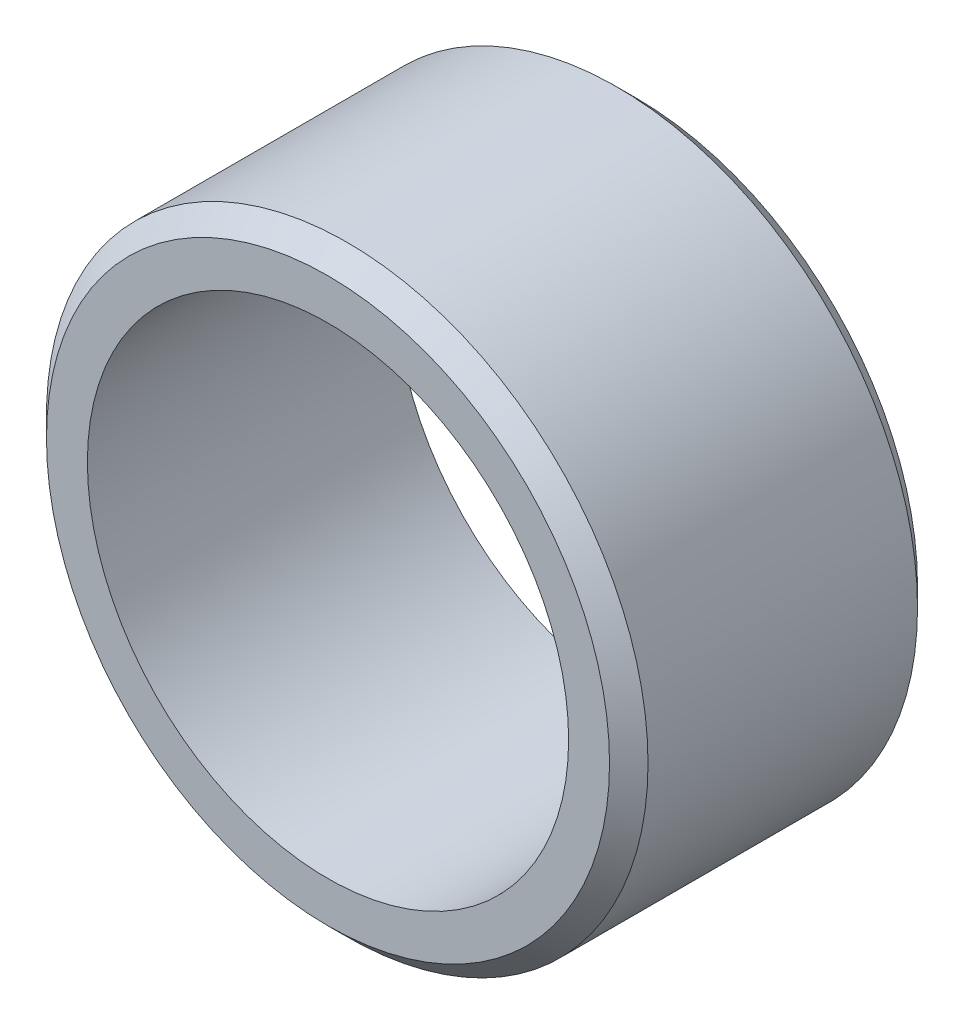
SolidWorks part; units mm, degrees
material "6061-T6 (SS)"
ref_plane "Front Plane" through (0, 0, 0) normal (0, 0, 1) x (1, 0, 0)
ref_plane "Top Plane" through (0, 0, 0) normal (0, 1, 0) x (1, 0, 0)
ref_plane "Right Plane" through (0, 0, 0) normal (1, 0, 0) x (0, 0, -1)
sketch "Sketch1" plane through (0, 0, 0) normal (0, 0, 1) x (1, 0, 0)
  circle A0 centre (0, 0) radius 6.35
  circle A1 centre (0, 0) radius 7.9375
  dimension "D1" = 12.7
  dimension "D2" = 15.875
extrude "Boss-Extrude1" add sketch "Sketch1" along normal blind 8.128
chamfer "Chamfer1" distance 0.508 angle 45 2 edges at (7.9375, 0, 0) (7.9375, 0, 8.128)
